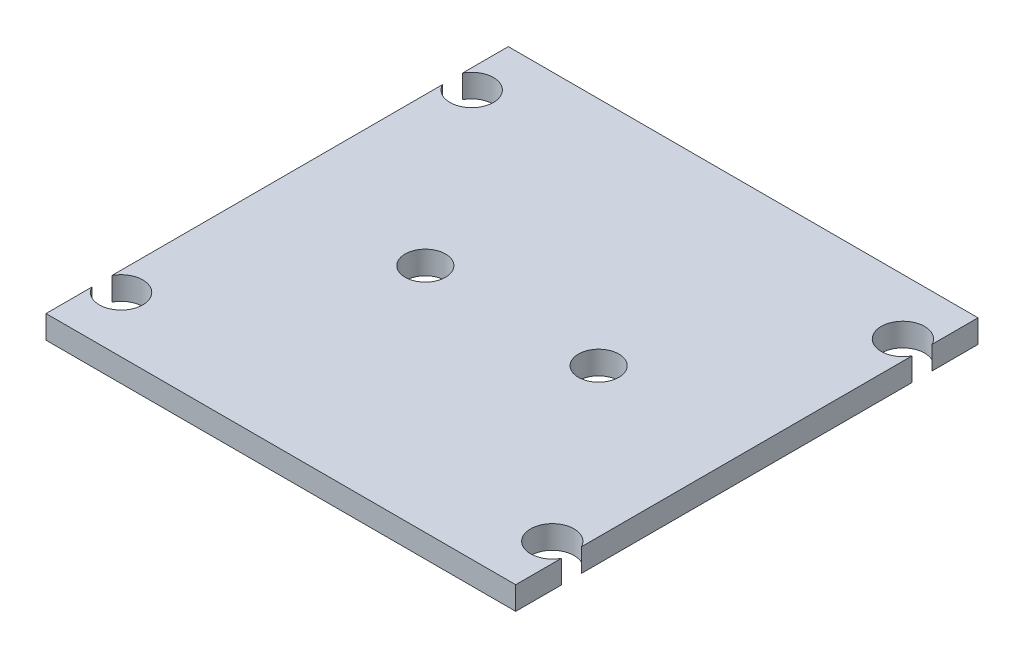
SolidWorks part; units mm, degrees
material "PLA"
ref_plane "Front Plane" through (0, 0, 0) normal (0, 0, 1) x (1, 0, 0)
ref_plane "Top Plane" through (0, 0, 0) normal (0, 1, 0) x (1, 0, 0)
ref_plane "Right Plane" through (0, 0, 0) normal (1, 0, 0) x (0, 0, -1)
sketch "Sketch1" plane through (0, 0, 0) normal (0, 1, 0) x (1, 0, 0)
  line L1 (-20.32, -20) -> (20.32, -20)
  line L2 (-20.32, -20) -> (-20.32, 20)
  line L3 (-20.32, 20) -> (20.32, 20)
  line L4 (20.32, -20) -> (20.32, 20)
  line L5 (-20.32, -20) -> (20.32, 20) construction
  line L6 (-20.32, 20) -> (20.32, -20) construction
  point P0 (0, 0)
  dimension "D1" = 40.64
  dimension "D2" = 40
extrude "Boss-Extrude1" add sketch "Sketch1" along normal blind 2
sketch "Sketch2" plane through (0, 2, 0) normal (0, 1, 0) x (1, 0, 0)
  line L0 (-20.32, 20) -> (-20.32, 16.3226) construction
  line L1 (-20.32, 20) -> (-20.32, -20) construction
  line L2 (-20.32, 16.3226) -> (-17.174, 16.3226) construction
  line L3 (-17.174, 16.3226) -> (-17.174, 15.0999) construction
  line L4 (-17.174, 15.0999) -> (-16.7779, 15.0999) construction
  line L5 (-16.7779, 15.0999) -> (-16.7779, 13.3356) construction
  line L6 (-16.7779, 13.3356) -> (-19.0658, 13.3356) construction
  line L7 (-1.1, 0) -> (1.1, 0) construction
  line L8 (0, -1.1) -> (0, 1.1) construction
  line L9 (-16.7779, 15.0999) -> (-16.7779, 1.5919) construction
  line L10 (-16.7779, 1.5919) -> (-6.773, 1.5919) construction
  line L11 (-6.773, 1.5919) -> (-6.773, -1.5919) construction
  line L12 (-6.773, -1.5919) -> (-9.2471, -1.5919) construction
  line L13 (-9.2471, -1.5919) -> (-9.2471, 0) construction
  line L14 (-7.498, 0) -> (7.498, 0) construction
  circle A0 centre (-18.6542, 15.1675) radius 1.8775
  circle A1 centre (-18.6542, -15.1675) radius 1.8775
  circle A2 centre (18.6542, -15.1675) radius 1.8775
  circle A3 centre (18.6542, 15.1675) radius 1.8775
  circle A4 centre (-7.498, 0) radius 1.7492
  circle A5 centre (7.498, 0) radius 1.7492
  dimension "D1" = 3.146
  dimension "D2" = 3.6774
  dimension "D3" = 2.2879
  dimension "D4" = 3.1837
  dimension "D5" = 2.4741
extrude "Cut-Extrude1" cut sketch "Sketch2" against normal through all both and the other way through all
